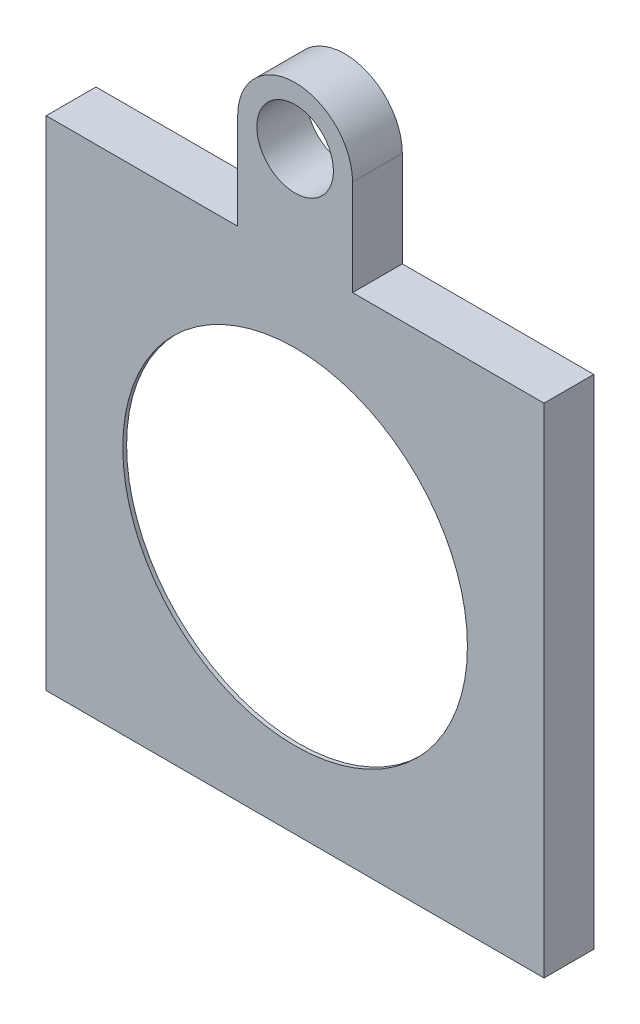
SolidWorks part; units mm, degrees
ref_plane "前视基准面" through (0, 0, 0) normal (0, 0, 1) x (1, 0, 0)
ref_plane "上视基准面" through (0, 0, 0) normal (0, 1, 0) x (1, 0, 0)
ref_plane "右视基准面" through (0, 0, 0) normal (1, 0, 0) x (0, 0, -1)
sketch "草图1" plane through (0, 0, 0) normal (0, 0, 1) x (1, 0, 0)
  line L0 (6.5, 6.5) -> (6.5, -6.5)
  line L1 (6, 6) -> (-6, 6)
  line L2 (6, 6) -> (6, -6)
  line L3 (6, -6) -> (-6, -6)
  line L4 (-6, 6) -> (-6, -6)
  line L5 (6, 6) -> (-6, -6) construction
  line L6 (6, -6) -> (-6, 6) construction
  line L7 (6.5, -6.5) -> (-6.5, -6.5)
  line L8 (-6.5, 6.5) -> (-6.5, -6.5)
  line L9 (6.5, 6.5) -> (-6.5, 6.5)
  point P0 (0, 0)
  dimension "D1" = 12
  dimension "D2" = 12
  dimension "D3" = 0.5
extrude "凸台-拉伸1" add sketch "草图1" along normal blind 1.2
sketch "草图2" plane through (0, 0, 1.2) normal (0, 0, 1) x (1, 0, 0)
  line L1 (-6.5, -6.5) -> (6.5, -6.5)
  line L2 (-6.5, -6.5) -> (-6.5, 6.5)
  line L3 (-6.5, 6.5) -> (6.5, 6.5)
  line L4 (6.5, -6.5) -> (6.5, 6.5)
  line L5 (-6.5, -6.5) -> (6.5, 6.5) construction
  line L6 (-6.5, 6.5) -> (6.5, -6.5) construction
  circle A1 centre (0, 0) radius 4.5
  point P0 (0, 0)
  dimension "D3" = 9
  dimension "D1" = 13
  dimension "D2" = 13
extrude "凸台-拉伸2" add sketch "草图2" along normal blind 0.1 contours A1
sketch "草图9" plane through (0, 0, 1.3) normal (0, 0, 1) x (1, 0, 0)
sketch "草图3" plane through (0, 6.5, 0) normal (0, 1, 0) x (1, 0, 0)
  line L0 (6.5, -1.3) -> (-6.5, -1.3) construction
  line L1 (1.5, 0) -> (-1.5, 0)
  line L2 (1.5, 0) -> (1.5, -1.3)
  line L3 (1.5, -1.3) -> (-1.5, -1.3)
  line L4 (-1.5, 0) -> (-1.5, -1.3)
  line L5 (1.5, 0) -> (-1.5, -1.3) construction
  line L6 (1.5, -1.3) -> (-1.5, 0) construction
  line L7 (6.5, 0) -> (-6.5, 0) construction
  point P0 (0, -0.65)
  dimension "D1" = 3
extrude "凸台-拉伸3" add sketch "草图3" along normal blind 4
sketch "草图4" plane through (0, 0, 1.3) normal (0, 0, 1) x (1, 0, 0)
  line L0 (-1.5, 9) -> (-1.5, 10.5)
  line L1 (-1.5, 10.5) -> (1.5, 10.5)
  line L2 (1.5, 10.5) -> (1.5, 9)
  circle A0 centre (0, 9) radius 1.5
  line M3 (1.5, 6.5) -> (1.5, 10.5)
  line M4 (1.5, 10.5) -> (-1.5, 10.5)
  line M5 (-1.5, 10.5) -> (-1.5, 6.5)
extrude "切除-拉伸1" cut sketch "草图4" against normal blind 4 contours A0 L1 M5 | A0 M3 M4
sketch "草图5" plane through (0, 0, 1.3) normal (0, 0, 1) x (1, 0, 0)
  circle A0 centre (0, 9) radius 1
  dimension "D2" = 2
  dimension "D1" = 9
extrude "切除-拉伸2" cut sketch "草图5" against normal blind 4 contours A0
